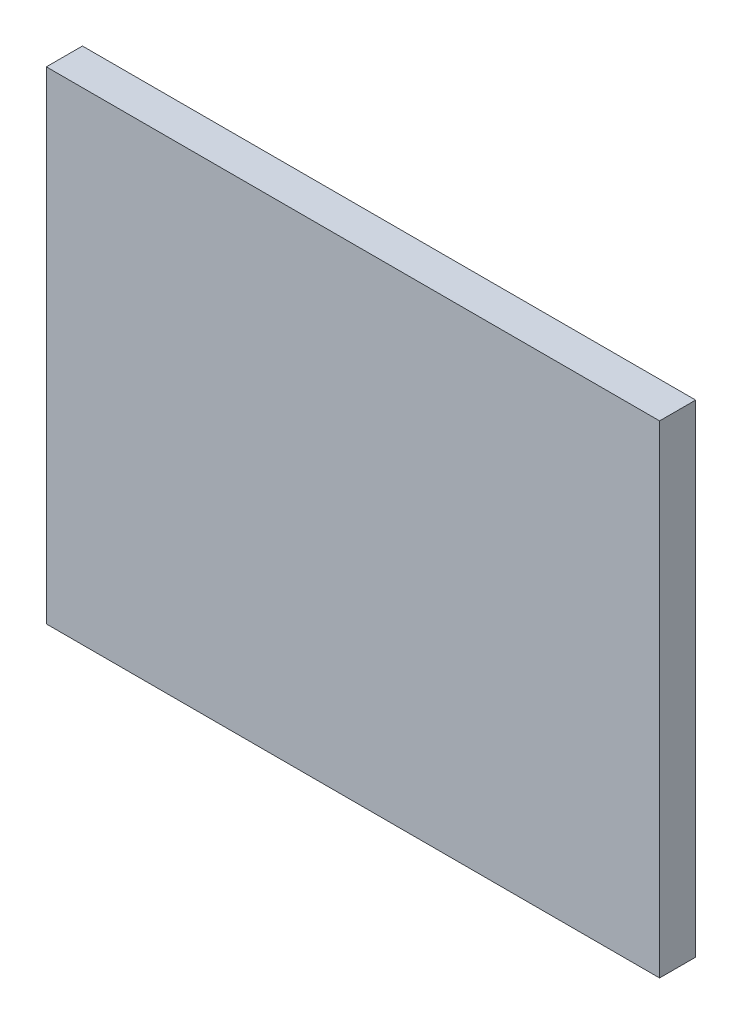
SolidWorks part; units mm, degrees
material "MDF"
ref_plane "Front Plane" through (0, 0, 0) normal (0, 0, 1) x (1, 0, 0)
ref_plane "Top Plane" through (0, 0, 0) normal (0, 1, 0) x (1, 0, 0)
ref_plane "Right Plane" through (0, 0, 0) normal (1, 0, 0) x (0, 0, -1)
sketch "Sketch1" plane through (0, 0, 0) normal (0, 0, 1) x (1, 0, 0)
  line L1 (-107.95, -84.9312) -> (107.95, -84.9312)
  line L2 (-107.95, -84.9312) -> (-107.95, 84.9313)
  line L3 (-107.95, 84.9313) -> (107.95, 84.9313)
  line L4 (107.95, -84.9312) -> (107.95, 84.9313)
  line L5 (-107.95, -84.9312) -> (107.95, 84.9313) construction
  line L6 (-107.95, 84.9313) -> (107.95, -84.9312) construction
  point P0 (0, 0)
  dimension "D1" = 215.9
  dimension "D2" = 169.8625
extrude "Boss-Extrude1" add sketch "Sketch1" along normal blind 12.7
